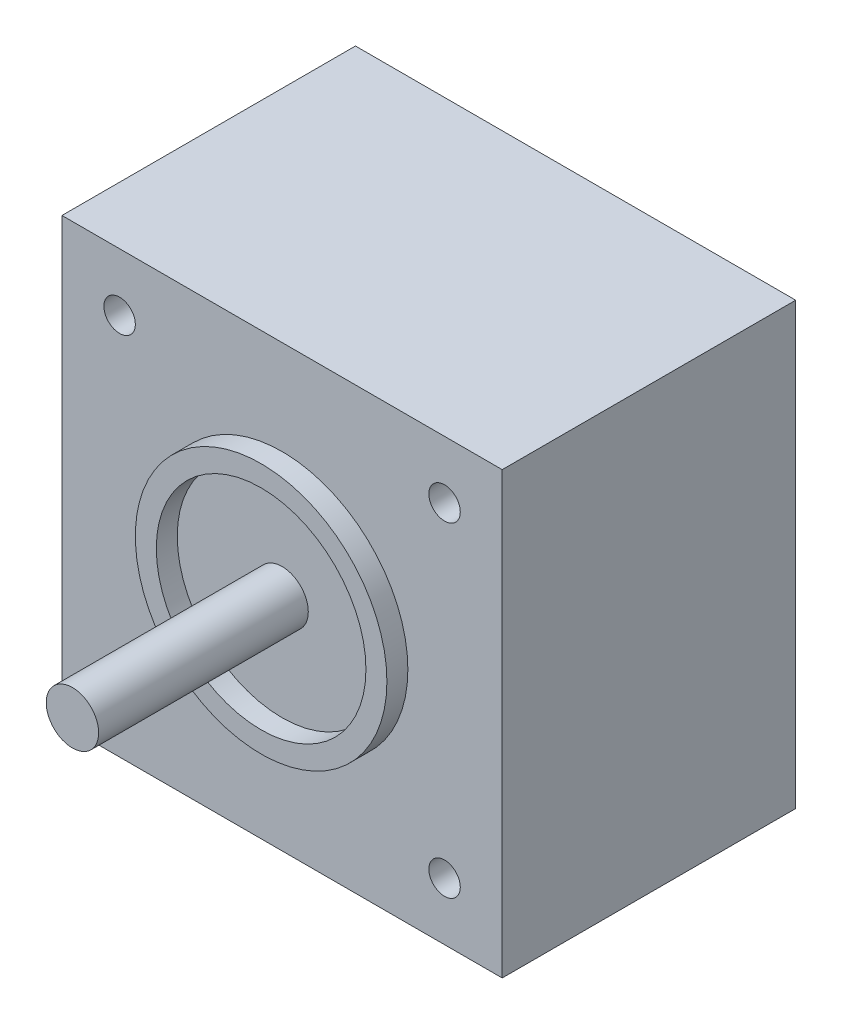
SolidWorks part; units mm, degrees
ref_plane "Front Plane" through (0, 0, 0) normal (0, 0, 1) x (1, 0, 0)
ref_plane "Top Plane" through (0, 0, 0) normal (0, 1, 0) x (1, 0, 0)
ref_plane "Right Plane" through (0, 0, 0) normal (1, 0, 0) x (0, 0, -1)
sketch "Sketch2" plane through (0, 0, 0) normal (0, 0, 1) x (1, 0, 0)
  line L1 (-21, 21) -> (21, 21)
  line L2 (-21, 21) -> (-21, -21)
  line L3 (-21, -21) -> (21, -21)
  line L4 (21, 21) -> (21, -21)
  line L5 (-21, 21) -> (21, -21) construction
  line L6 (-21, -21) -> (21, 21) construction
  point P0 (0, 0)
  dimension "D1" = 42
  dimension "D2" = 42
extrude "Boss-Extrude1" add sketch "Sketch2" along normal blind 28
sketch "Sketch3" plane through (0, 0, 28) normal (0, 0, 1) x (1, 0, 0)
  circle A0 centre (15.5, 15.5) radius 1.5
  circle A1 centre (-15.5, 15.5) radius 1.5
  circle A2 centre (-15.5, -15.5) radius 1.5
  circle A3 centre (15.5, -15.5) radius 1.5
  dimension "D1" = 3
  dimension "D2" = 3
  dimension "D3" = 3
  dimension "D4" = 3
  dimension "D5" = 15.5
  dimension "D6" = 15.5
  dimension "D7" = 15.5
  dimension "D8" = 15.5
  dimension "D9" = 15.5
  dimension "D10" = 15.5
  dimension "D11" = 15.5
  dimension "D12" = 15.5
extrude "Cut-Extrude1" cut sketch "Sketch3" against normal blind 10
sketch "Sketch4" plane through (0, 0, 28) normal (0, 0, 1) x (1, 0, 0)
  circle A0 centre (0, 0) radius 12
  dimension "D1" = 24
extrude "Boss-Extrude2" add sketch "Sketch4" along normal blind 2
sketch "Sketch5" plane through (0, 0, 30) normal (0, 0, 1) x (1, 0, 0)
  circle A0 centre (0, 0) radius 10
  dimension "D1" = 20
extrude "Cut-Extrude2" cut sketch "Sketch5" against normal blind 2
sketch "Sketch6" plane through (0, 0, 28) normal (0, 0, 1) x (1, 0, 0)
  circle A0 centre (0, 0) radius 2.5
  dimension "D1" = 5
extrude "Boss-Extrude3" add sketch "Sketch6" along normal blind 20
sketch "Sketch7" plane through (0, -21, 0) normal (0, -1, 0) x (1, 0, 0)
  line L0 (-21, 0) -> (21, 0) construction
  line L1 (7.5, 0) -> (-7.5, 0)
  line L2 (7.5, 0) -> (7.5, 8)
  line L3 (7.5, 8) -> (-7.5, 8)
  line L4 (-7.5, 0) -> (-7.5, 8)
  line L5 (-21, 28) -> (-21, 0) construction
  dimension "D1" = 8
  dimension "D2" = 15
  dimension "D3" = 13.5
extrude "Boss-Extrude4" add sketch "Sketch7" along normal blind 6
sketch "Sketch8" plane through (0, -27, 0) normal (0, -1, 0) x (-1, 0, 0)
  line L0 (-7.5, -8) -> (7.5, -8) construction
  line L1 (6.5, -7) -> (-6.5, -7)
  line L2 (6.5, -7) -> (6.5, -1)
  line L3 (6.5, -1) -> (-6.5, -1)
  line L4 (-6.5, -7) -> (-6.5, -1)
  line L5 (-7.5, 0) -> (-7.5, -8) construction
  line L6 (7.5, 0) -> (-7.5, 0) construction
  line L7 (7.5, -8) -> (7.5, 0) construction
  dimension "D1" = 1
  dimension "D2" = 1
  dimension "D3" = 1
  dimension "D4" = 1
extrude "Cut-Extrude4" cut sketch "Sketch8" against normal blind 6
